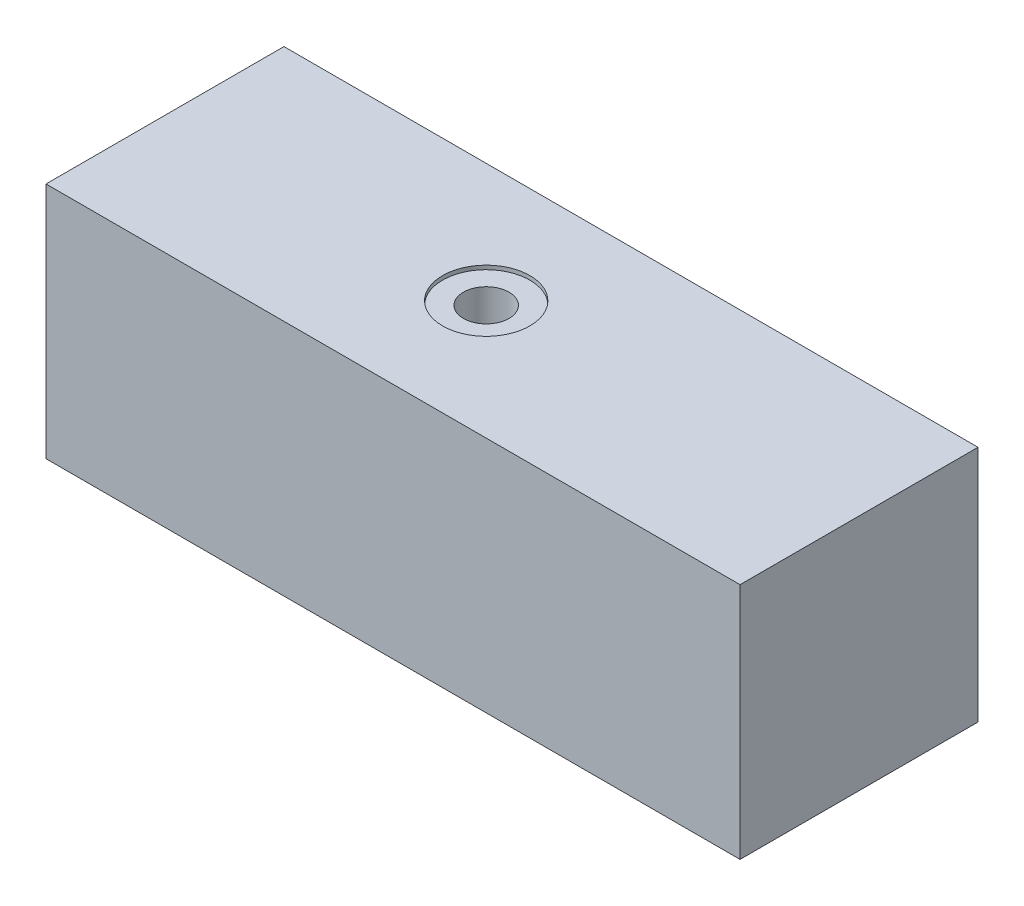
SolidWorks part; units mm, degrees
material "Plomb pur"
ref_plane "Plan de face" through (0, 0, 0) normal (0, 0, 1) x (1, 0, 0)
ref_plane "Plan de dessus" through (0, 0, 0) normal (0, 1, 0) x (1, 0, 0)
ref_plane "Plan de droite" through (0, 0, 0) normal (1, 0, 0) x (0, 0, -1)
sketch "Esquisse1" plane through (0, 0, 0) normal (0, 0, 1) x (1, 0, 0)
  line L0 (-87.5, 34) -> (-87.5, -26)
  line L1 (87.5, -26) -> (87.5, 34)
  line L2 (87.5, 34) -> (-87.5, 34)
  line L3 (-87.5, -26) -> (87.5, -26)
  dimension "D1" = 60
  dimension "D2" = 175
  dimension "D3" = 87.5
extrude "Extrusion1" add sketch "Esquisse1" along normal blind 60
hole_wizard "Perçage1" positions "Esquisse3D1" profile "Esquisse3" legacy end condition through all
sketch3d "Esquisse3D1"
  line L0 (-87.5, 34, 60) -> (-87.5, 34, 0) construction
  line L1 (87.5, 34, 60) -> (-87.5, 34, 60) construction
  point P0 (-6.5, 34, 30)
  dimension "D1" = 81
  dimension "D2" = 30
sketch "Esquisse3" plane through (-6.5, 34, 30) normal (1, 0, 0) x (0, 0, 1)
  line L0 (0, 0) -> (0, 60)
  line L1 (0, 60) -> (5.75, 60)
  line L2 (5.75, 60) -> (5.75, 1)
  line L3 (5.75, 1) -> (11, 1)
  line L4 (11, 1) -> (11, 0)
  line L5 (11, 0) -> (0, 0)
  line L6 (0, 110) -> (0, -10) construction
  dimension "Diamètre" = 11.5
  dimension "Profondeur" = 60
  dimension "Diamètre chambrage" = 22
  dimension "Profondeur chambrage" = 1
